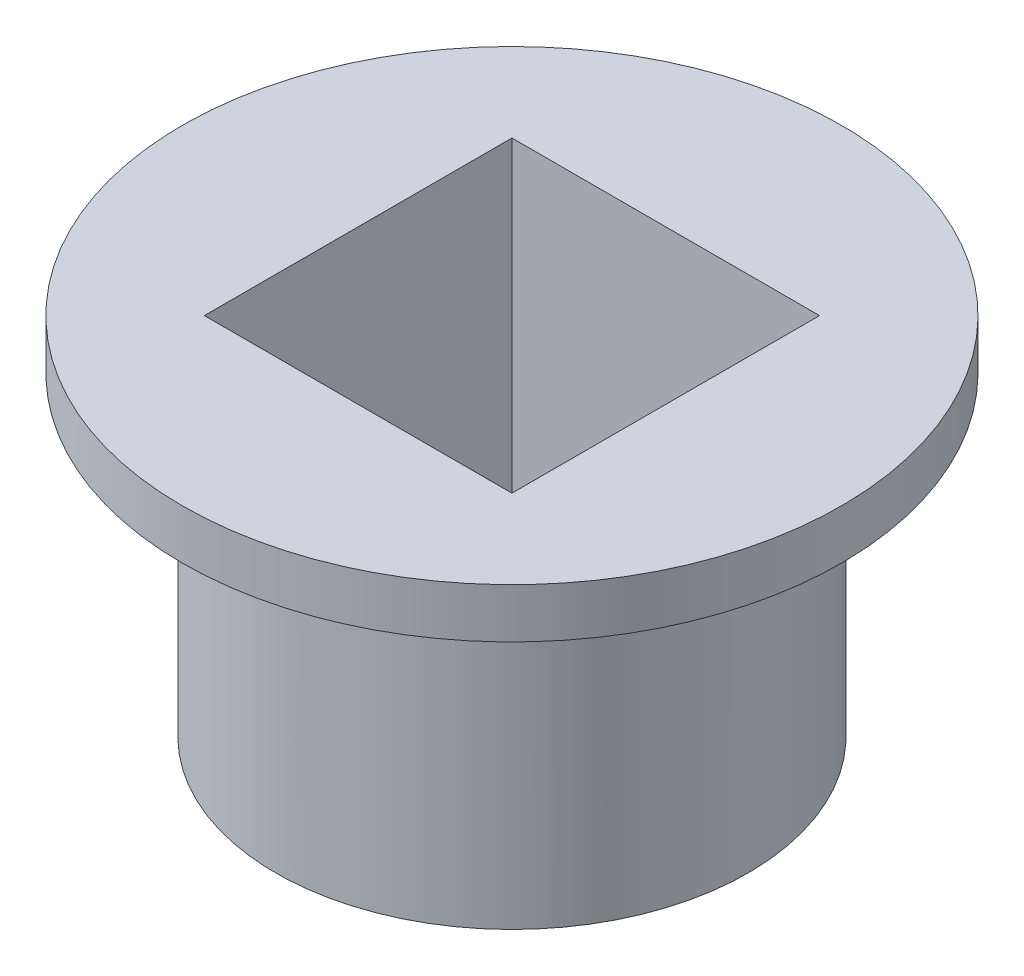
SolidWorks part; units mm, degrees
ref_plane "Front Plane" through (0, 0, 0) normal (0, 0, 1) x (1, 0, 0)
ref_plane "Top Plane" through (0, 0, 0) normal (0, 1, 0) x (1, 0, 0)
ref_plane "Right Plane" through (0, 0, 0) normal (1, 0, 0) x (0, 0, -1)
sketch "Sketch1" plane through (0, 0, 0) normal (0, 1, 0) x (1, 0, 0)
  line L0 (-6.2, -6.2) -> (6.2, -6.2)
  line L1 (-6.2, -6.2) -> (-6.2, 6.2)
  line L2 (6.2, -6.2) -> (6.2, 6.2)
  line L3 (-6.2, 6.2) -> (6.2, 6.2)
  line L4 (-6.2, -6.2) -> (6.2, 6.2) construction
  line L5 (6.2, -6.2) -> (-6.2, 6.2) construction
  circle A0 centre (0, 0) radius 9.525
  point P1 (0, 0)
  dimension "D3" = 19.05
  dimension "D1" = 12.4
  dimension "D2" = 12.4
extrude "Boss-Extrude1" add sketch "Sketch1" along normal blind 12.7
sketch "Sketch2" plane through (0, 12.7, 0) normal (0, 1, 0) x (1, 0, 0)
  circle A1 centre (0, 0) radius 9.525 construction
  circle A3 centre (0, 0) radius 13.2875
  circle A4 centre (0, 0) radius 9.525
  dimension "D1" = 26.575
extrude "Boss-Extrude3" add sketch "Sketch2" against normal blind 2
sketch "Sketch3" plane through (0, 0, 0) normal (0, -1, 0) x (1, 0, 0)
  circle A0 centre (0, 0) radius 9.525 construction
  circle A1 centre (0, 0) radius 9.525
  circle A2 centre (0, 0) radius 4.7
  dimension "D1" = 9.4
extrude "Boss-Extrude4" add sketch "Sketch3" along normal blind 2
